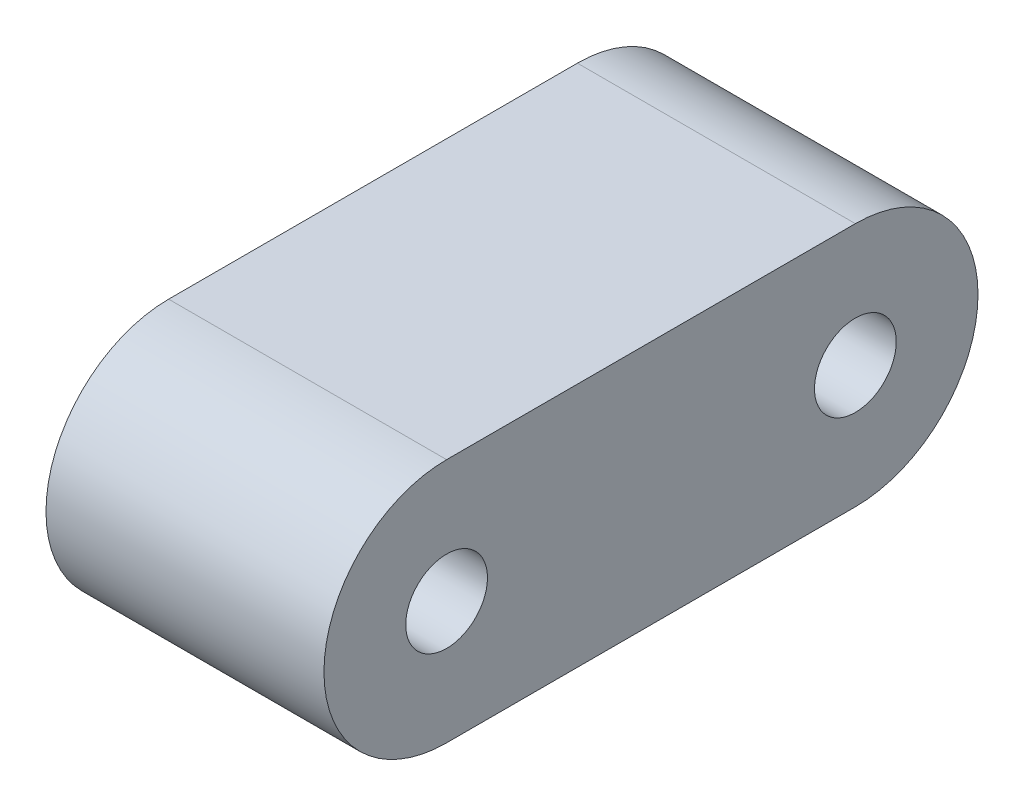
SolidWorks part; units mm, degrees
ref_plane "Alzado" through (0, 0, 0) normal (0, 0, 1) x (1, 0, 0)
ref_plane "Planta" through (0, 0, 0) normal (0, 1, 0) x (1, 0, 0)
ref_plane "Vista lateral" through (0, 0, 0) normal (1, 0, 0) x (0, 0, -1)
sketch "Croquis1" plane through (0, 0, 0) normal (1, 0, 0) x (0, 0, -1)
  line L0 (-12.5, 0) -> (12.5, 0) construction
  line L1 (-12.5, 7.5) -> (12.5, 7.5)
  line L2 (-12.5, -7.5) -> (12.5, -7.5)
  circle A0 centre (-12.5, 0) radius 2.5
  circle A1 centre (12.5, 0) radius 2.5
  arc A2 (-12.5, 7.5) -> (-12.5, -7.5) centre (-12.5, 0) ccw
  arc A3 (12.5, -7.5) -> (12.5, 7.5) centre (12.5, 0) ccw
  point P3 (0, 0)
  dimension "D1" = 5
  dimension "D3" = 15
  dimension "D2" = 25
extrude "Saliente-Extruir1" add sketch "Croquis1" along normal mid plane 17
